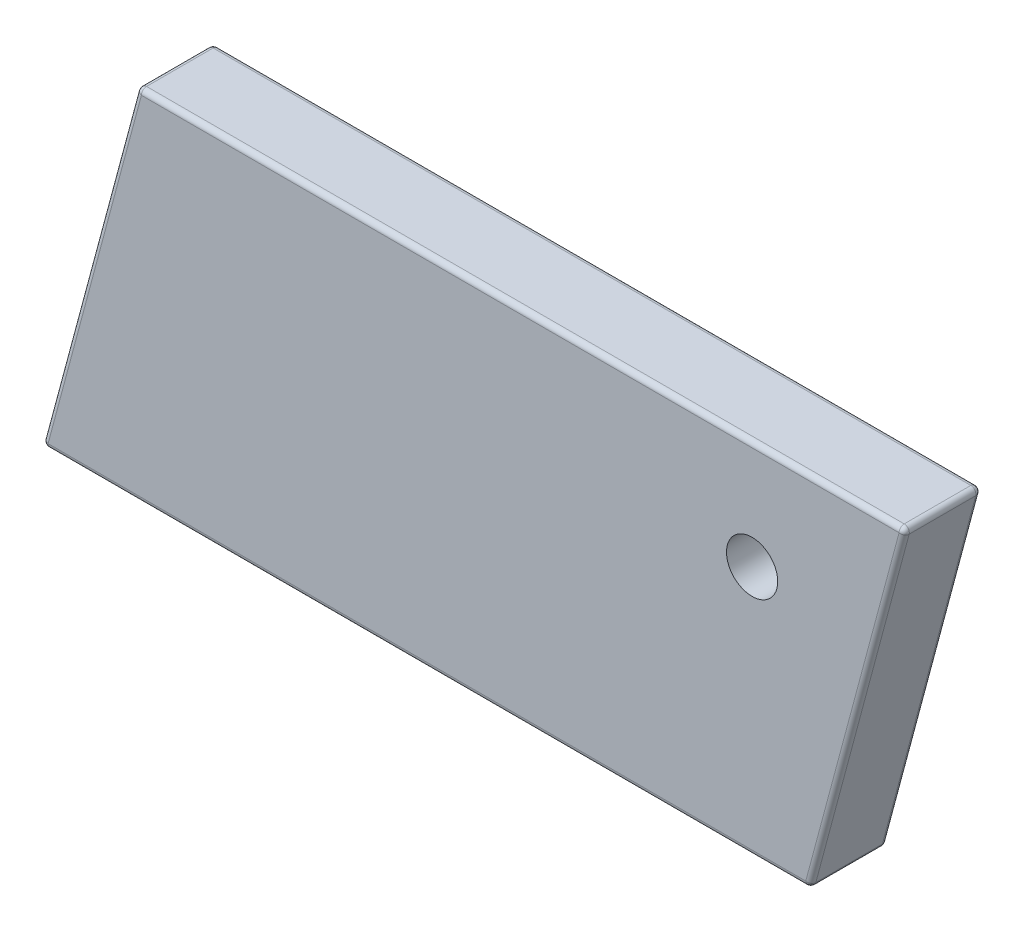
SolidWorks part; units mm, degrees
ref_plane "Front Plane" through (0, 0, 0) normal (0, 0, 1) x (1, 0, 0)
ref_plane "Top Plane" through (0, 0, 0) normal (0, 1, 0) x (1, 0, 0)
ref_plane "Right Plane" through (0, 0, 0) normal (1, 0, 0) x (0, 0, -1)
sketch "Sketch1" plane through (0, 0, 0) normal (0, 0, 1) x (1, 0, 0)
  line L0 (0, 0) -> (23.8207, 88.9)
  line L1 (23.8207, 88.9) -> (214.3207, 88.9)
  line L2 (214.3207, 88.9) -> (190.5, 0)
  line L3 (190.5, 0) -> (0, 0)
  dimension "D1" = 75
  dimension "D2" = 190.5
  dimension "D3" = 88.9
extrude "Boss-Extrude1" add sketch "Sketch1" along normal blind 19.05
sketch "Sketch2" plane through (0, 0, 19.05) normal (0, 0, 1) x (1, 0, 0)
  circle A0 centre (176.2207, 62.0838) radius 6.35
  point P2 (0, 0)
  point P3 (0, 0)
  dimension "D1" = 12.7
  dimension "D2" = 38.1
extrude "Cut-Extrude1" cut sketch "Sketch2" against normal blind 19.05
fillet "Fillet1" radius 1.27 12 edges at (95.25, 0, 19.05) (95.25, 0, 0) (190.5, 0, 9.525) (202.4103, 44.45, 19.05) (214.3207, 88.9, 9.525) (202.4103, 44.45, 0) (23.8207, 88.9, 9.525) (11.9103, 44.45, 19.05) (0, 0, 9.525) (11.9103, 44.45, 0) (119.0707, 88.9, 0) (119.0707, 88.9, 19.05)
